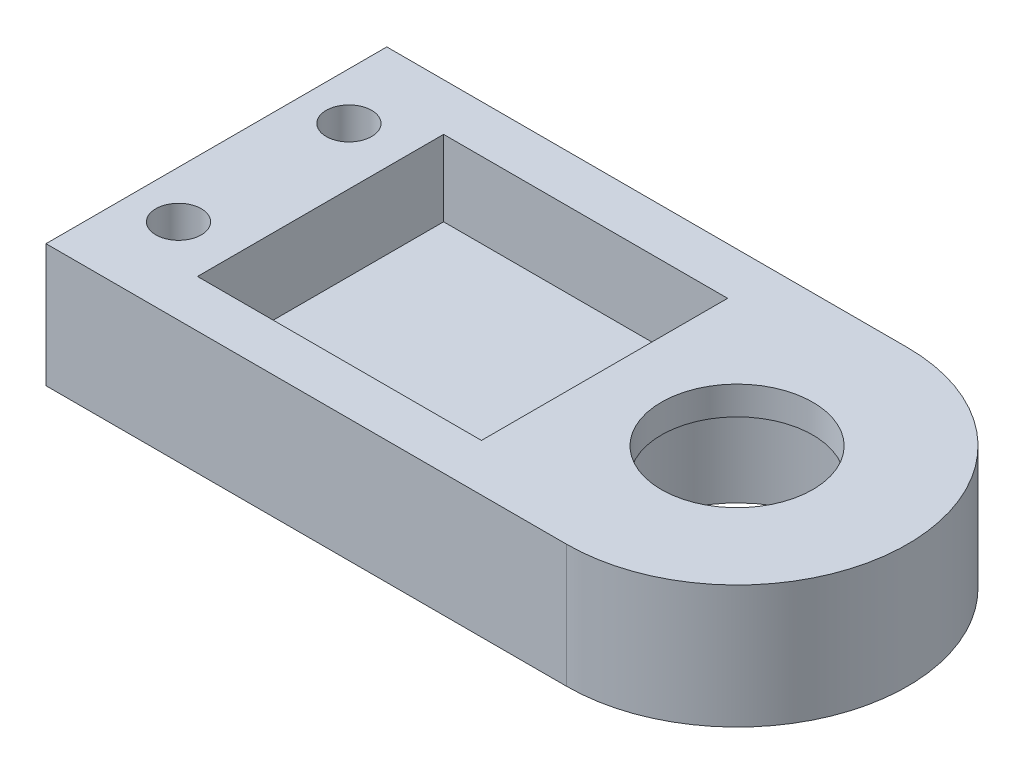
SolidWorks part; units mm, degrees
material "ABS"
ref_plane "Front Plane" through (0, 0, 0) normal (0, 0, 1) x (1, 0, 0)
ref_plane "Top Plane" through (0, 0, 0) normal (0, 1, 0) x (1, 0, 0)
ref_plane "Right Plane" through (0, 0, 0) normal (1, 0, 0) x (0, 0, -1)
ref_plane "Y+24_80" through (0, 24.8, 0) normal (0, 1, 0) x (1, 0, 0)
sketch "Sketch1" plane through (0, 24.8, 0) normal (0, 1, 0) x (1, 0, 0)
  line L0 (5.5, 9) -> (-22, 9)
  line L1 (-22, 9) -> (-22, -9)
  line L2 (-22, -9) -> (5.5, -9)
  arc A0 (5.5, -9) -> (5.5, 9) centre (5.5, 0) ccw
extrude "Boss-Extrude1" add sketch "Sketch1" along normal blind 6.5
sketch "Sketch2" plane through (0, 24.8, 0) normal (0, 1, 0) x (1, 0, 0)
  circle A0 centre (5.5, 0) radius 5.5
extrude "Cut-Extrude2" cut sketch "Sketch2" along normal blind 5
ref_plane "Y+29_80" through (0, 29.8, 0) normal (0, 1, 0) x (1, 0, 0)
sketch "Sketch3" plane through (0, 29.8, 0) normal (0, 1, 0) x (1, 0, 0)
  circle A0 centre (5.5, 0) radius 4
extrude "Cut-Extrude4" cut sketch "Sketch3" along normal blind 1.5
hole_wizard "M2 Clearance Hole1" positions "Sketch5" profile "Sketch4" hole size "M2" standard "ISO"
sketch "Sketch5" plane through (0, 31.3, 0) normal (0, 1, 0) x (1, 0, 0)
  point P0 (-19.5, -4.5)
sketch "Sketch4" plane through (-19.5, 31.3, 4.5) normal (1, 0, 0) x (0, 0, 1)
  line L0 (0, 0) -> (0, 6.5)
  line L1 (0, 6.5) -> (1.2, 6.5)
  line L2 (1.2, 6.5) -> (1.2, 0)
  line L5 (1.2, 0) -> (0, 0)
  line L11 (0, -6.35) -> (0, 107.95) construction
  dimension "Thru Hole Dia." = 2.4
  dimension "Thru Hole Depth" = 6.5
hole_wizard "M2 Clearance Hole2" positions "Sketch7" profile "Sketch6" hole size "M2" standard "ISO"
sketch "Sketch7" plane through (0, 31.3, 0) normal (0, 1, 0) x (1, 0, 0)
  point P0 (-19.5, 4.5)
sketch "Sketch6" plane through (-19.5, 31.3, -4.5) normal (1, 0, 0) x (0, 0, 1)
  line L0 (0, 0) -> (0, 6.5)
  line L1 (0, 6.5) -> (1.2, 6.5)
  line L2 (1.2, 6.5) -> (1.2, 0)
  line L5 (1.2, 0) -> (0, 0)
  line L11 (0, -6.35) -> (0, 107.95) construction
  dimension "Thru Hole Dia." = 2.4
  dimension "Thru Hole Depth" = 6.5
ref_plane "Y+31_30" through (0, 31.3, 0) normal (0, 1, 0) x (1, 0, 0)
sketch "Sketch8" plane through (0, 31.3, 0) normal (0, 1, 0) x (1, 0, 0)
  line L1 (-16.5, -6.5) -> (-1.5, -6.5)
  line L2 (-16.5, -6.5) -> (-16.5, 6.5)
  line L3 (-16.5, 6.5) -> (-1.5, 6.5)
  line L4 (-1.5, -6.5) -> (-1.5, 6.5)
extrude "Cut-Extrude5" cut sketch "Sketch8" against normal blind 4
